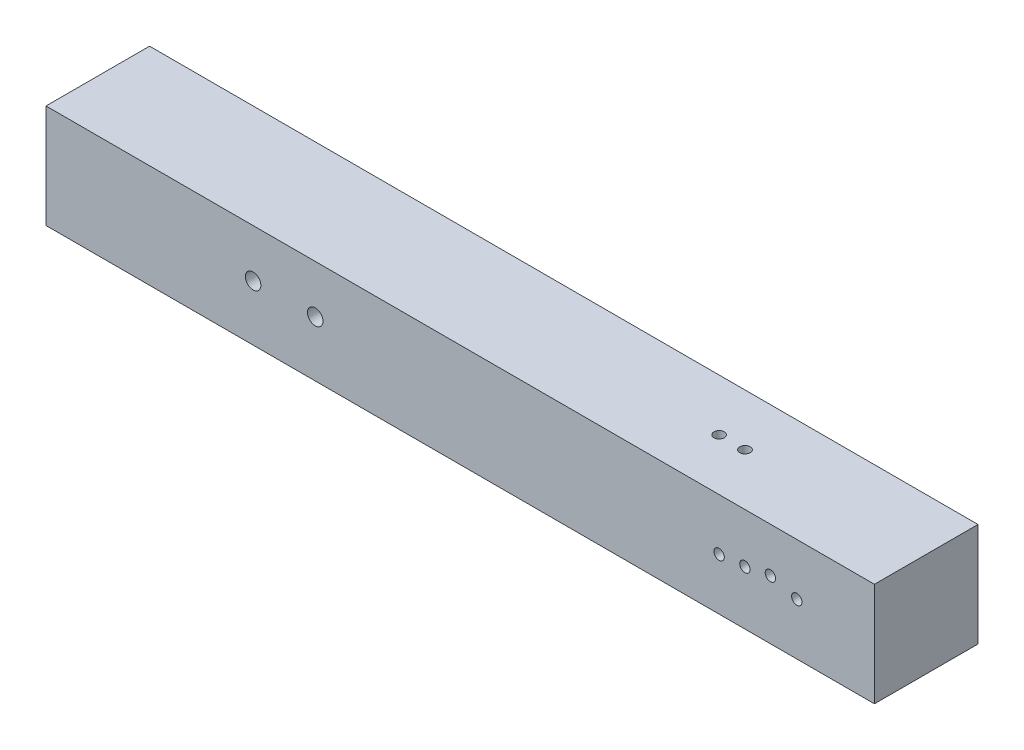
SolidWorks part; units mm, degrees
material "ABS"
ref_plane "Front Plane" through (0, 0, 0) normal (0, 0, 1) x (1, 0, 0)
ref_plane "Top Plane" through (0, 0, 0) normal (0, 1, 0) x (1, 0, 0)
ref_plane "Right Plane" through (0, 0, 0) normal (1, 0, 0) x (0, 0, -1)
sketch "Sketch2" plane through (0, 0, 0) normal (0, 0, 1) x (1, 0, 0)
  line L1 (0, 0) -> (203.2, 0)
  line L2 (0, 0) -> (0, 25.4)
  line L3 (0, 25.4) -> (203.2, 25.4)
  line L4 (203.2, 0) -> (203.2, 25.4)
  dimension "D1" = 25.4
  dimension "D2" = 203.2
extrude "Boss-Extrude1" add sketch "Sketch2" along normal mid plane 25.4
curve "Curve5"
  spline degree 3 poles (25.4, 0, 0.032) (25.3951, 0, 0.0327) (25.3753, 0, 0.0355) (25.3309, 0, 0.0417) (25.257, 0, 0.052) (25.1537, 0, 0.0664) (25.0214, 0, 0.0846) (24.8603, 0, 0.1068) (24.6708, 0, 0.1326) (24.4533, 0, 0.1619) (24.2084, 0, 0.1946) (23.9366, 0, 0.2304) (23.6385, 0, 0.2691) (23.3149, 0, 0.3106) (22.9666, 0, 0.3545) (22.5942, 0, 0.4008) (22.1987, 0, 0.449) (21.7811, 0, 0.499) (21.3422, 0, 0.5505) (20.8832, 0, 0.6032) (20.405, 0, 0.6571) (19.9089, 0, 0.7116) (19.3959, 0, 0.7667) (18.8673, 0, 0.8219) (18.3242, 0, 0.8772) (17.7681, 0, 0.9321) (17.2001, 0, 0.9864) (16.6216, 0, 1.0399) (16.0339, 0, 1.0922) (15.4384, 0, 1.143) (14.8366, 0, 1.1921) (14.2297, 0, 1.2391) (13.6193, 0, 1.2836) (13.0067, 0, 1.3254) (12.3935, 0, 1.3642) (11.7809, 0, 1.3995) (11.1705, 0, 1.4311) (10.5636, 0, 1.4587) (9.9618, 0, 1.4818) (9.3663, 0, 1.5004) (8.7786, 0, 1.514) (8.2001, 0, 1.5224) (7.632, 0, 1.5254) (7.0758, 0, 1.5227) (6.5327, 0, 1.5144) (6.0041, 0, 1.5) (5.491, 0, 1.4798) (4.9948, 0, 1.4535) (4.5166, 0, 1.4212) (4.0575, 0, 1.3829) (3.6185, 0, 1.3388) (3.2008, 0, 1.2888) (2.8052, 0, 1.2334) (2.4327, 0, 1.1725) (2.0841, 0, 1.1064) (1.7603, 0, 1.0355) (1.462, 0, 0.96) (1.1898, 0, 0.8801) (0.9445, 0, 0.7962) (0.7264, 0, 0.7086) (0.536, 0, 0.6175) (0.3737, 0, 0.523) (0.2396, 0, 0.4254) (0.1341, 0, 0.3245) (0.0574, 0, 0.22) (0.0105, 0, 0.1114) (-0.0051, 0, 0) (0.0105, 0, -0.1114) (0.0574, 0, -0.22) (0.1341, 0, -0.3245) (0.2396, 0, -0.4254) (0.3737, 0, -0.523) (0.536, 0, -0.6175) (0.7264, 0, -0.7086) (0.9445, 0, -0.7962) (1.1898, 0, -0.8801) (1.462, 0, -0.96) (1.7603, 0, -1.0355) (2.0841, 0, -1.1064) (2.4327, 0, -1.1725) (2.8052, 0, -1.2334) (3.2008, 0, -1.2888) (3.6185, 0, -1.3388) (4.0575, 0, -1.3829) (4.5166, 0, -1.4212) (4.9948, 0, -1.4535) (5.491, 0, -1.4798) (6.0041, 0, -1.5) (6.5327, 0, -1.5144) (7.0758, 0, -1.5227) (7.632, 0, -1.5254) (8.2001, 0, -1.5224) (8.7786, 0, -1.514) (9.3663, 0, -1.5004) (9.9618, 0, -1.4818) (10.5636, 0, -1.4587) (11.1705, 0, -1.4311) (11.7809, 0, -1.3995) (12.3935, 0, -1.3642) (13.0067, 0, -1.3254) (13.6193, 0, -1.2836) (14.2297, 0, -1.2391) (14.8366, 0, -1.1921) (15.4384, 0, -1.143) (16.0339, 0, -1.0922) (16.6216, 0, -1.0399) (17.2001, 0, -0.9864) (17.7681, 0, -0.9321) (18.3242, 0, -0.8772) (18.8673, 0, -0.8219) (19.3959, 0, -0.7667) (19.9089, 0, -0.7116) (20.405, 0, -0.6571) (20.8832, 0, -0.6032) (21.3422, 0, -0.5505) (21.7811, 0, -0.499) (22.1987, 0, -0.449) (22.5942, 0, -0.4008) (22.9666, 0, -0.3545) (23.3149, 0, -0.3106) (23.6385, 0, -0.2691) (23.9366, 0, -0.2304) (24.2084, 0, -0.1946) (24.4533, 0, -0.1619) (24.6708, 0, -0.1326) (24.8603, 0, -0.1068) (25.0214, 0, -0.0846) (25.1537, 0, -0.0664) (25.257, 0, -0.052) (25.3309, 0, -0.0417) (25.3753, 0, -0.0355) (25.3951, 0, -0.0327) (25.4, 0, -0.032) knots 0 0 0 0 0.000289 0.001156 0.002598 0.004612 0.007194 0.010336 0.014031 0.018272 0.023046 0.028343 0.03415 0.040454 0.047238 0.054489 0.062187 0.070314 0.078852 0.08778 0.097078 0.106722 0.116691 0.126961 0.137507 0.148306 0.159331 0.170556 0.181957 0.193504 0.205171 0.216932 0.228758 0.240621 0.252495 0.26435 0.276161 0.287898 0.299536 0.311047 0.322405 0.333584 0.344559 0.355306 0.3658 0.376018 0.385937 0.395538 0.404798 0.413699 0.422221 0.430349 0.438066 0.445357 0.452209 0.458612 0.464554 0.47003 0.475035 0.479569 0.483637 0.48725 0.490431 0.493219 0.495674 0.497891 0.5 0.502109 0.504326 0.506781 0.509569 0.51275 0.516363 0.520431 0.524965 0.52997 0.535446 0.541388 0.547791 0.554643 0.561934 0.569651 0.577779 0.586301 0.595202 0.604462 0.614063 0.623982 0.6342 0.644694 0.655441 0.666416 0.677595 0.688953 0.700464 0.712102 0.723839 0.73565 0.747505 0.759379 0.771242 0.783068 0.794829 0.806496 0.818043 0.829444 0.840669 0.851694 0.862493 0.873039 0.883309 0.893278 0.902922 0.91222 0.921148 0.929686 0.937813 0.945511 0.952762 0.959546 0.96585 0.971657 0.976954 0.981728 0.985969 0.989664 0.992806 0.995388 0.997402 0.998844 0.999711 1 1 1 1
sketch "Sketch8" plane through (0, 0, 0) normal (0, -1, 0) x (1, 0, 0)
  line L0 (203.2, 12.7) -> (203.2, -12.7) construction
  line L1 (203.2, 0) -> (203.2, -0.128)
  spline S1 degree 3 poles (203.2, 0) (203.1901, 0.0014) (203.1506, 0.0069) (202.9929, 0.029) (202.7567, 0.062) (202.4427, 0.1053) (202.1205, 0.1496) (201.7415, 0.2012) (201.3066, 0.2598) (200.8167, 0.3251) (200.2731, 0.3968) (199.6771, 0.4743) (199.0299, 0.5571) (198.0694, 0.6784) (197.0461, 0.8042) (195.9622, 0.9339) (195.0845, 1.037) (194.1664, 1.1425) (193.21, 1.2501) (192.2177, 1.3592) (191.1918, 1.4693) (190.1345, 1.5798) (189.0485, 1.6903) (187.9361, 1.8001) (186.8001, 1.9089) (185.6431, 2.0158) (184.4678, 2.1204) (183.2769, 2.2221) (182.0731, 2.3202) (180.8594, 2.4142) (179.6386, 2.5033) (178.4135, 2.5869) (177.1869, 2.6644) (175.5572, 2.7583) (173.9348, 2.8376) (171.9316, 2.9147) (170.3546, 2.9582) (168.8001, 2.9808) (167.664, 2.9867) (166.5516, 2.9815) (165.4655, 2.9648) (164.4082, 2.9361) (163.3821, 2.8956) (162.3897, 2.843) (161.4332, 2.7784) (160.515, 2.7019) (159.6371, 2.6135) (158.8016, 2.5137) (158.0104, 2.4027) (157.2654, 2.2809) (156.5682, 2.1489) (155.9206, 2.0071) (155.324, 1.856) (154.7797, 1.6963) (154.2889, 1.5285) (153.8527, 1.3532) (153.4719, 1.1709) (153.1473, 0.982) (152.8793, 0.7868) (152.6682, 0.585) (152.5148, 0.376) (152.421, 0.1588) (152.3898, -0.064) (152.421, -0.2869) (152.5148, -0.504) (152.6682, -0.713) (152.8793, -0.9148) (153.1473, -1.11) (153.4719, -1.2989) (153.8527, -1.4812) (154.2889, -1.6565) (154.7797, -1.8243) (155.324, -1.984) (155.9206, -2.1351) (156.5682, -2.2769) (157.2654, -2.409) (158.0104, -2.5307) (158.8016, -2.6417) (159.6371, -2.7415) (160.515, -2.8299) (161.4332, -2.9064) (162.3897, -2.971) (163.3821, -3.0236) (164.4082, -3.0641) (165.4655, -3.0928) (166.5516, -3.1095) (167.664, -3.1147) (168.8001, -3.1088) (170.3546, -3.0862) (172.3368, -3.0316) (174.3396, -2.947) (175.9618, -2.863) (177.1869, -2.7924) (178.4135, -2.7149) (179.6386, -2.6313) (180.8594, -2.5422) (182.0731, -2.4482) (183.2769, -2.3501) (184.4678, -2.2485) (185.6431, -2.1438) (186.8001, -2.0369) (187.9361, -1.9282) (189.0485, -1.8183) (190.1345, -1.7078) (191.1918, -1.5973) (192.2177, -1.4872) (193.21, -1.3781) (194.1664, -1.2705) (195.0845, -1.165) (195.9622, -1.0619) (197.0461, -0.9322) (198.0694, -0.8064) (199.0299, -0.6851) (199.6771, -0.6023) (200.2731, -0.5248) (200.8167, -0.4532) (201.3066, -0.3878) (201.7415, -0.3292) (202.1205, -0.2776) (202.4427, -0.2333) (202.7567, -0.19) (202.9929, -0.157) (203.1506, -0.135) (203.1901, -0.1294) (203.2, -0.128) knots 0 0 0 0 0.000289 0.001156 0.004612 0.007194 0.010336 0.014031 0.018272 0.023046 0.028343 0.03415 0.040454 0.047238 0.062187 0.070314 0.078852 0.08778 0.097078 0.106722 0.116691 0.126961 0.137507 0.148306 0.159331 0.170556 0.181957 0.193504 0.205171 0.216932 0.228758 0.240621 0.252495 0.26435 0.287898 0.299536 0.322405 0.333584 0.344559 0.355306 0.3658 0.376018 0.385937 0.395538 0.404798 0.413699 0.422221 0.430349 0.438066 0.445357 0.452209 0.458612 0.464554 0.47003 0.475035 0.479569 0.483637 0.48725 0.490431 0.493219 0.495674 0.497891 0.5 0.502109 0.504326 0.506781 0.509569 0.51275 0.516363 0.520431 0.524965 0.52997 0.535446 0.541388 0.547791 0.554643 0.561934 0.569651 0.577779 0.586301 0.595202 0.604462 0.614063 0.623982 0.6342 0.644694 0.655441 0.666416 0.677595 0.700464 0.723839 0.73565 0.747505 0.759379 0.771242 0.783068 0.794829 0.806496 0.818043 0.829444 0.840669 0.851694 0.862493 0.873039 0.883309 0.893278 0.902922 0.91222 0.921148 0.929686 0.937813 0.952762 0.959546 0.96585 0.971657 0.976954 0.981728 0.985969 0.989664 0.992806 0.995388 0.998844 0.999711 1 1 1 1
sketch "Sketch10" plane through (0, 0, 0) normal (0, 0, 1) x (1, 0, 0)
  line L0 (228.6, 0) -> (254, -43.9941)
  line L1 (152.4, 0) -> (203.2, 0) construction
  line L2 (0, 0) -> (203.2, 0) construction
  line L3 (203.2, 0) -> (203.2, -43.9941)
  dimension "D1" = 60
  dimension "D2" = 50.8
ref_plane "Plane1" through (0, -43.9941, 0) normal (0, -1, 0) x (-1, 0, 0)
curve "Curve6"
  spline degree 3 poles (25.4, 0, 0.032) (25.3951, 0, 0.0327) (25.3753, 0, 0.0355) (25.3309, 0, 0.0417) (25.257, 0, 0.052) (25.1537, 0, 0.0664) (25.0214, 0, 0.0846) (24.8603, 0, 0.1068) (24.6708, 0, 0.1326) (24.4533, 0, 0.1619) (24.2084, 0, 0.1946) (23.9366, 0, 0.2304) (23.6385, 0, 0.2691) (23.3149, 0, 0.3106) (22.9666, 0, 0.3545) (22.5942, 0, 0.4008) (22.1987, 0, 0.449) (21.7811, 0, 0.499) (21.3422, 0, 0.5505) (20.8832, 0, 0.6032) (20.405, 0, 0.6571) (19.9089, 0, 0.7116) (19.3959, 0, 0.7667) (18.8673, 0, 0.8219) (18.3242, 0, 0.8772) (17.7681, 0, 0.9321) (17.2001, 0, 0.9864) (16.6216, 0, 1.0399) (16.0339, 0, 1.0922) (15.4384, 0, 1.143) (14.8366, 0, 1.1921) (14.2297, 0, 1.2391) (13.6193, 0, 1.2836) (13.0067, 0, 1.3254) (12.3935, 0, 1.3642) (11.7809, 0, 1.3995) (11.1705, 0, 1.4311) (10.5636, 0, 1.4587) (9.9618, 0, 1.4818) (9.3663, 0, 1.5004) (8.7786, 0, 1.514) (8.2001, 0, 1.5224) (7.632, 0, 1.5254) (7.0758, 0, 1.5227) (6.5327, 0, 1.5144) (6.0041, 0, 1.5) (5.491, 0, 1.4798) (4.9948, 0, 1.4535) (4.5166, 0, 1.4212) (4.0575, 0, 1.3829) (3.6185, 0, 1.3388) (3.2008, 0, 1.2888) (2.8052, 0, 1.2334) (2.4327, 0, 1.1725) (2.0841, 0, 1.1064) (1.7603, 0, 1.0355) (1.462, 0, 0.96) (1.1898, 0, 0.8801) (0.9445, 0, 0.7962) (0.7264, 0, 0.7086) (0.536, 0, 0.6175) (0.3737, 0, 0.523) (0.2396, 0, 0.4254) (0.1341, 0, 0.3245) (0.0574, 0, 0.22) (0.0105, 0, 0.1114) (-0.0051, 0, 0) (0.0105, 0, -0.1114) (0.0574, 0, -0.22) (0.1341, 0, -0.3245) (0.2396, 0, -0.4254) (0.3737, 0, -0.523) (0.536, 0, -0.6175) (0.7264, 0, -0.7086) (0.9445, 0, -0.7962) (1.1898, 0, -0.8801) (1.462, 0, -0.96) (1.7603, 0, -1.0355) (2.0841, 0, -1.1064) (2.4327, 0, -1.1725) (2.8052, 0, -1.2334) (3.2008, 0, -1.2888) (3.6185, 0, -1.3388) (4.0575, 0, -1.3829) (4.5166, 0, -1.4212) (4.9948, 0, -1.4535) (5.491, 0, -1.4798) (6.0041, 0, -1.5) (6.5327, 0, -1.5144) (7.0758, 0, -1.5227) (7.632, 0, -1.5254) (8.2001, 0, -1.5224) (8.7786, 0, -1.514) (9.3663, 0, -1.5004) (9.9618, 0, -1.4818) (10.5636, 0, -1.4587) (11.1705, 0, -1.4311) (11.7809, 0, -1.3995) (12.3935, 0, -1.3642) (13.0067, 0, -1.3254) (13.6193, 0, -1.2836) (14.2297, 0, -1.2391) (14.8366, 0, -1.1921) (15.4384, 0, -1.143) (16.0339, 0, -1.0922) (16.6216, 0, -1.0399) (17.2001, 0, -0.9864) (17.7681, 0, -0.9321) (18.3242, 0, -0.8772) (18.8673, 0, -0.8219) (19.3959, 0, -0.7667) (19.9089, 0, -0.7116) (20.405, 0, -0.6571) (20.8832, 0, -0.6032) (21.3422, 0, -0.5505) (21.7811, 0, -0.499) (22.1987, 0, -0.449) (22.5942, 0, -0.4008) (22.9666, 0, -0.3545) (23.3149, 0, -0.3106) (23.6385, 0, -0.2691) (23.9366, 0, -0.2304) (24.2084, 0, -0.1946) (24.4533, 0, -0.1619) (24.6708, 0, -0.1326) (24.8603, 0, -0.1068) (25.0214, 0, -0.0846) (25.1537, 0, -0.0664) (25.257, 0, -0.052) (25.3309, 0, -0.0417) (25.3753, 0, -0.0355) (25.3951, 0, -0.0327) (25.4, 0, -0.032) knots 0 0 0 0 0.000289 0.001156 0.002598 0.004612 0.007194 0.010336 0.014031 0.018272 0.023046 0.028343 0.03415 0.040454 0.047238 0.054489 0.062187 0.070314 0.078852 0.08778 0.097078 0.106722 0.116691 0.126961 0.137507 0.148306 0.159331 0.170556 0.181957 0.193504 0.205171 0.216932 0.228758 0.240621 0.252495 0.26435 0.276161 0.287898 0.299536 0.311047 0.322405 0.333584 0.344559 0.355306 0.3658 0.376018 0.385937 0.395538 0.404798 0.413699 0.422221 0.430349 0.438066 0.445357 0.452209 0.458612 0.464554 0.47003 0.475035 0.479569 0.483637 0.48725 0.490431 0.493219 0.495674 0.497891 0.5 0.502109 0.504326 0.506781 0.509569 0.51275 0.516363 0.520431 0.524965 0.52997 0.535446 0.541388 0.547791 0.554643 0.561934 0.569651 0.577779 0.586301 0.595202 0.604462 0.614063 0.623982 0.6342 0.644694 0.655441 0.666416 0.677595 0.688953 0.700464 0.712102 0.723839 0.73565 0.747505 0.759379 0.771242 0.783068 0.794829 0.806496 0.818043 0.829444 0.840669 0.851694 0.862493 0.873039 0.883309 0.893278 0.902922 0.91222 0.921148 0.929686 0.937813 0.945511 0.952762 0.959546 0.96585 0.971657 0.976954 0.981728 0.985969 0.989664 0.992806 0.995388 0.997402 0.998844 0.999711 1 1 1 1
sketch "Sketch11" plane through (0, -43.9941, 0) normal (0, -1, 0) x (-1, 0, 0)
  line L0 (-203.2, 0.064) -> (-203.2, 0)
  spline S1 degree 3 poles (-203.2, 0) (-203.1951, -0.0007) (-203.1753, -0.0035) (-203.0964, -0.0145) (-202.9784, -0.031) (-202.8214, -0.0526) (-202.6603, -0.0748) (-202.4708, -0.1006) (-202.2533, -0.1299) (-202.0084, -0.1626) (-201.7366, -0.1984) (-201.4385, -0.2371) (-201.1149, -0.2786) (-200.6347, -0.3392) (-200.123, -0.4021) (-199.5811, -0.467) (-199.1422, -0.5185) (-198.6832, -0.5712) (-198.205, -0.6251) (-197.7089, -0.6796) (-197.1959, -0.7347) (-196.6673, -0.7899) (-196.1242, -0.8452) (-195.5681, -0.9001) (-195.0001, -0.9544) (-194.4216, -1.0079) (-193.8339, -1.0602) (-193.2384, -1.111) (-192.6366, -1.1601) (-192.0297, -1.2071) (-191.4193, -1.2516) (-190.8067, -1.2934) (-190.1935, -1.3322) (-189.3786, -1.3792) (-188.5674, -1.4188) (-187.5658, -1.4574) (-186.7773, -1.4791) (-186.0001, -1.4904) (-185.432, -1.4934) (-184.8758, -1.4907) (-184.3327, -1.4824) (-183.8041, -1.468) (-183.291, -1.4478) (-182.7948, -1.4215) (-182.3166, -1.3892) (-181.8575, -1.3509) (-181.4185, -1.3067) (-181.0008, -1.2568) (-180.6052, -1.2014) (-180.2327, -1.1405) (-179.8841, -1.0744) (-179.5603, -1.0035) (-179.262, -0.928) (-178.9898, -0.8481) (-178.7445, -0.7642) (-178.5264, -0.6766) (-178.336, -0.5854) (-178.1737, -0.491) (-178.0396, -0.3934) (-177.9341, -0.2925) (-177.8574, -0.188) (-177.8105, -0.0794) (-177.7949, 0.032) (-177.8105, 0.1434) (-177.8574, 0.252) (-177.9341, 0.3565) (-178.0396, 0.4574) (-178.1737, 0.555) (-178.336, 0.6495) (-178.5264, 0.7406) (-178.7445, 0.8282) (-178.9898, 0.9121) (-179.262, 0.992) (-179.5603, 1.0675) (-179.8841, 1.1385) (-180.2327, 1.2045) (-180.6052, 1.2654) (-181.0008, 1.3208) (-181.4185, 1.3708) (-181.8575, 1.4149) (-182.3166, 1.4532) (-182.7948, 1.4855) (-183.291, 1.5118) (-183.8041, 1.5321) (-184.3327, 1.5464) (-184.8758, 1.5547) (-185.432, 1.5574) (-186.0001, 1.5544) (-186.7773, 1.5431) (-187.7684, 1.5158) (-188.7698, 1.4735) (-189.5809, 1.4315) (-190.1935, 1.3962) (-190.8067, 1.3574) (-191.4193, 1.3156) (-192.0297, 1.2711) (-192.6366, 1.2241) (-193.2384, 1.175) (-193.8339, 1.1242) (-194.4216, 1.0719) (-195.0001, 1.0184) (-195.5681, 0.9641) (-196.1242, 0.9092) (-196.6673, 0.8539) (-197.1959, 0.7987) (-197.7089, 0.7436) (-198.205, 0.6891) (-198.6832, 0.6352) (-199.1422, 0.5825) (-199.5811, 0.531) (-200.123, 0.4661) (-200.6347, 0.4032) (-201.1149, 0.3426) (-201.4385, 0.3012) (-201.7366, 0.2624) (-202.0084, 0.2266) (-202.2533, 0.1939) (-202.4708, 0.1646) (-202.6603, 0.1388) (-202.8214, 0.1166) (-202.9784, 0.095) (-203.0964, 0.0785) (-203.1753, 0.0675) (-203.1951, 0.0647) (-203.2, 0.064) knots 0 0 0 0 0.000289 0.001156 0.004612 0.007194 0.010336 0.014031 0.018272 0.023046 0.028343 0.03415 0.040454 0.047238 0.062187 0.070314 0.078852 0.08778 0.097078 0.106722 0.116691 0.126961 0.137507 0.148306 0.159331 0.170556 0.181957 0.193504 0.205171 0.216932 0.228758 0.240621 0.252495 0.26435 0.287898 0.299536 0.322405 0.333584 0.344559 0.355306 0.3658 0.376018 0.385937 0.395538 0.404798 0.413699 0.422221 0.430349 0.438066 0.445357 0.452209 0.458612 0.464554 0.47003 0.475035 0.479569 0.483637 0.48725 0.490431 0.493219 0.495674 0.497891 0.5 0.502109 0.504326 0.506781 0.509569 0.51275 0.516363 0.520431 0.524965 0.52997 0.535446 0.541388 0.547791 0.554643 0.561934 0.569651 0.577779 0.586301 0.595202 0.604462 0.614063 0.623982 0.6342 0.644694 0.655441 0.666416 0.677595 0.700464 0.723839 0.73565 0.747505 0.759379 0.771242 0.783068 0.794829 0.806496 0.818043 0.829444 0.840669 0.851694 0.862493 0.873039 0.883309 0.893278 0.902922 0.91222 0.921148 0.929686 0.937813 0.952762 0.959546 0.96585 0.971657 0.976954 0.981728 0.985969 0.989664 0.992806 0.995388 0.998844 0.999711 1 1 1 1
sketch "Sketch12" plane through (0, 0, -12.7) normal (0, 0, -1) x (-1, 0, 0)
  line L0 (-267.4072, 27.4646) -> (-234.4782, 27.4646) construction
  line L1 (-267.4072, 27.4646) -> (-261.0813, 28.018) construction
  line L2 (-267.4072, 27.4646) -> (-248.6466, 30.7726) construction
  line L3 (-267.4072, 27.4646) -> (-248.6466, 24.1566) construction
  line L4 (-267.4072, 27.4646) -> (-247.4604, 26.2092) construction
  circle A0 centre (-267.4072, 27.4646) radius 1.905
  circle A1 centre (-261.0813, 28.018) radius 1.905
  circle A2 centre (-254.7072, 27.4646) radius 1.905
  circle A3 centre (-248.6466, 24.1566) radius 1.905
  circle A4 centre (-248.6466, 30.7726) radius 1.905
  dimension "D1" = 3.81
  dimension "D2" = 12.7
  dimension "D3" = 6.35
  dimension "D4" = 5
  dimension "D5" = 10
  dimension "D6" = 19.05
  dimension "D7" = 10
  dimension "D8" = 19.05
sketch "Sketch13" plane through (0, 0, 12.7) normal (0, 0, 1) x (1, 0, 0)
  line L0 (0, 0) -> (203.2, 0) construction
  line L1 (165.1, 12.7) -> (184.15, 12.7) construction
  line L2 (165.1, 12.7) -> (177.6764, 14.4675) construction
  line L3 (165.1, 12.7) -> (171.4258, 13.2534) construction
  line L5 (203.2, 0) -> (203.2, 25.4) construction
  circle A0 centre (165.1, 12.7) radius 1.27
  circle A1 centre (184.15, 12.7) radius 1.27
  circle A2 centre (171.4258, 13.2534) radius 1.27
  circle A3 centre (177.6764, 14.4675) radius 1.27
  dimension "D1" = 2.54
  dimension "D7" = 38.1
  dimension "D2" = 6.35
  dimension "D3" = 5
  dimension "D4" = 12.7
  dimension "D5" = 8
  dimension "D6" = 19.05
  dimension "D8" = 12.7
extrude "Cut-Extrude2" cut sketch "Sketch13" against normal through all
ref_plane "Plane2" through (0, 0, 0) normal (0, 0, 1) x (1, 0, 0)
ref_plane "Plane3" through (155.575, 0, 0) normal (1, 0, 0) x (0, 0, -1)
sketch "Sketch18" plane through (0, 0, 0) normal (0, 0, 1) x (1, 0, 0)
  line L0 (152.4, 25.4) -> (153.67, 25.4)
  line L1 (153.67, 25.4) -> (153.67, 15.24)
  line L2 (153.67, 15.24) -> (152.4, 13.0403)
  line L3 (152.4, 13.0403) -> (152.4, 25.4)
  line L4 (203.2, 25.4) -> (0, 25.4) construction
  dimension "D1" = 1.27
  dimension "D2" = 10.16
  dimension "D3" = 30
  dimension "D4" = 50.8
revolve "Cut-Revolve2" cut sketch "Sketch18" angle 360 about L3
mirror "Mirror2" about plane through (155.575, 0, 0) normal (1, 0, 0) of "Cut-Revolve2"
sketch "Sketch16" plane through (0, 0, 12.7) normal (0, 0, 1) x (1, 0, 0)
  line L0 (0, 25.4) -> (0, 0) construction
  circle A0 centre (50.8, 13.6259) radius 1.905
  circle A1 centre (66.04, 13.6259) radius 1.905
  dimension "D1" = 3.81
  dimension "D2" = 15.24
  dimension "D3" = 50.8
extrude "Cut-Extrude4" cut sketch "Sketch16" against normal through all
